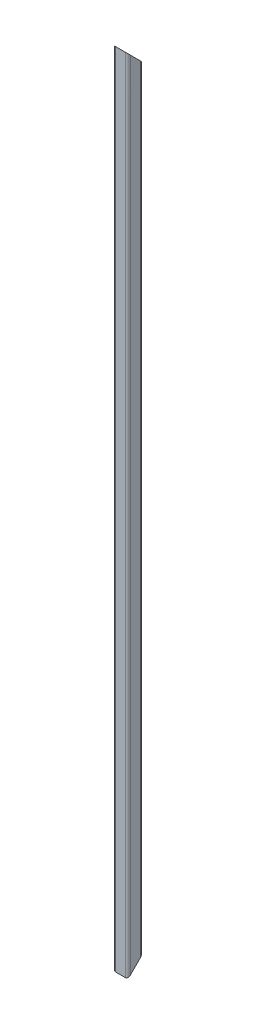
SolidWorks part; units mm, degrees
ref_plane "Спереди" through (0, 0, 0) normal (0, 0, 1) x (1, 0, 0)
ref_plane "Сверху" through (0, 0, 0) normal (0, 1, 0) x (1, 0, 0)
ref_plane "Справа" through (0, 0, 0) normal (1, 0, 0) x (0, 0, -1)
sketch "Эскиз1" plane through (0, 0, 0) normal (0, 1, 0) x (1, 0, 0)
  line L1 (-20, 30) -> (20, 30)
  line L2 (-30, 20) -> (-30, -20)
  line L3 (-20, -30) -> (20, -30)
  line L4 (30, 20) -> (30, -20)
  line L5 (-30, 30) -> (30, -30) construction
  line L6 (-30, -30) -> (30, 30) construction
  line L7 (-16, 26) -> (16, 26)
  line L8 (-26, 16) -> (-26, -16)
  line L9 (-16, -26) -> (16, -26)
  line L10 (26, 16) -> (26, -16)
  line L11 (-26, 26) -> (26, -26) construction
  line L12 (-26, -26) -> (26, 26) construction
  arc A0 (20, 30) -> (30, 20) centre (20, 20) cw
  arc A1 (-20, 30) -> (-30, 20) centre (-20, 20) ccw
  arc A2 (-30, -20) -> (-20, -30) centre (-20, -20) ccw
  arc A3 (20, -30) -> (30, -20) centre (20, -20) ccw
  arc A4 (16, -26) -> (26, -16) centre (16, -16) ccw
  arc A5 (16, 26) -> (26, 16) centre (16, 16) cw
  arc A6 (-16, 26) -> (-26, 16) centre (-16, 16) ccw
  arc A7 (-26, -16) -> (-16, -26) centre (-16, -16) ccw
  point P0 (0, 0)
  point P6 (0, 0)
  dimension "D5" = 10
  dimension "D1" = 60
  dimension "D2" = 60
  dimension "D3" = 4
  dimension "D4" = 4
extrude "Бобышка-Вытянуть1" add sketch "Эскиз1" along normal blind 3240
sketch "Эскиз2" plane through (30, 0, 0) normal (1, 0, 0) x (0, 0, -1)
  line L0 (-30, 0) -> (30, 0)
  line L1 (30, 0) -> (30, 60)
  line L2 (30, 3240) -> (30, 0) construction
  line L3 (30, 60) -> (-30, 0)
  line L4 (-30, 3240) -> (30, 3240)
  line L5 (30, 3240) -> (30, 3180)
  line L6 (30, 3180) -> (-30, 3240)
  dimension "D1" = 45
  dimension "D2" = 45
extrude "Вырез-Вытянуть1" cut sketch "Эскиз2" against normal through all
